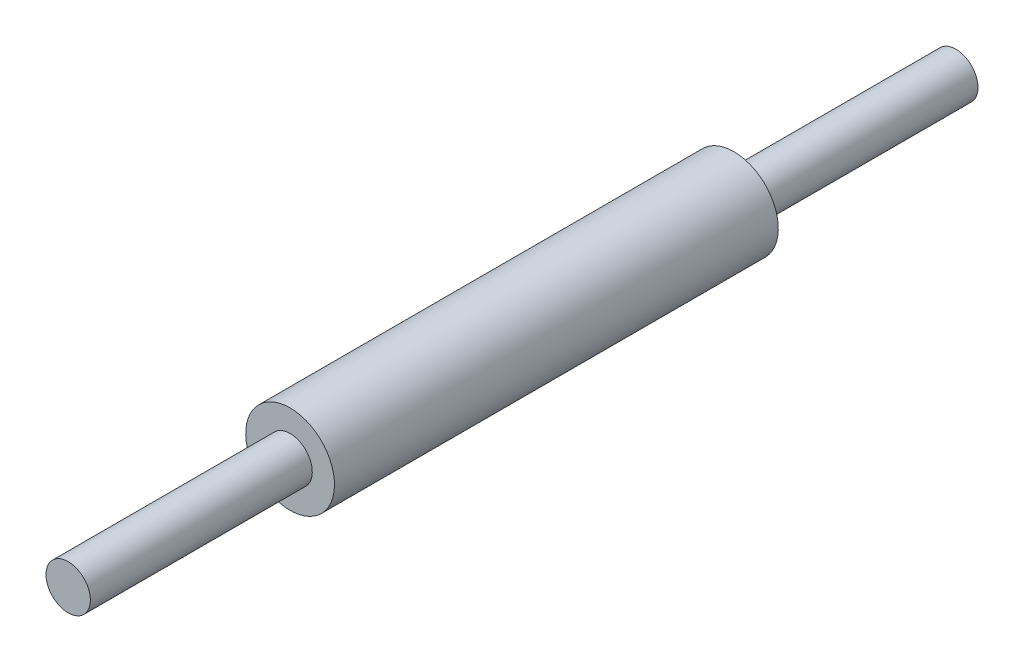
SolidWorks part; units mm, degrees
ref_plane "Front Plane" through (0, 0, 0) normal (0, 0, 1) x (1, 0, 0)
ref_plane "Top Plane" through (0, 0, 0) normal (0, 1, 0) x (1, 0, 0)
ref_plane "Right Plane" through (0, 0, 0) normal (1, 0, 0) x (0, 0, -1)
sketch "Sketch3" plane through (0, 0, 0) normal (1, 0, 0) x (0, 0, -1)
  line L0 (0, 0) -> (0, 3.175)
  line L1 (0, 3.175) -> (31.75, 3.175)
  line L2 (31.75, 3.175) -> (31.75, 6.35)
  line L3 (31.75, 6.35) -> (95.25, 6.35)
  line L4 (95.25, 6.35) -> (95.25, 3.175)
  line L5 (95.25, 3.175) -> (127, 3.175)
  line L6 (127, 3.175) -> (127, 0)
  line L7 (127, 0) -> (0, 0)
  dimension "D1" = 127
  dimension "D2" = 63.5
  dimension "D3" = 3.175
  dimension "D4" = 6.35
revolve "Revolve1" add sketch "Sketch3" angle 360 about L7
